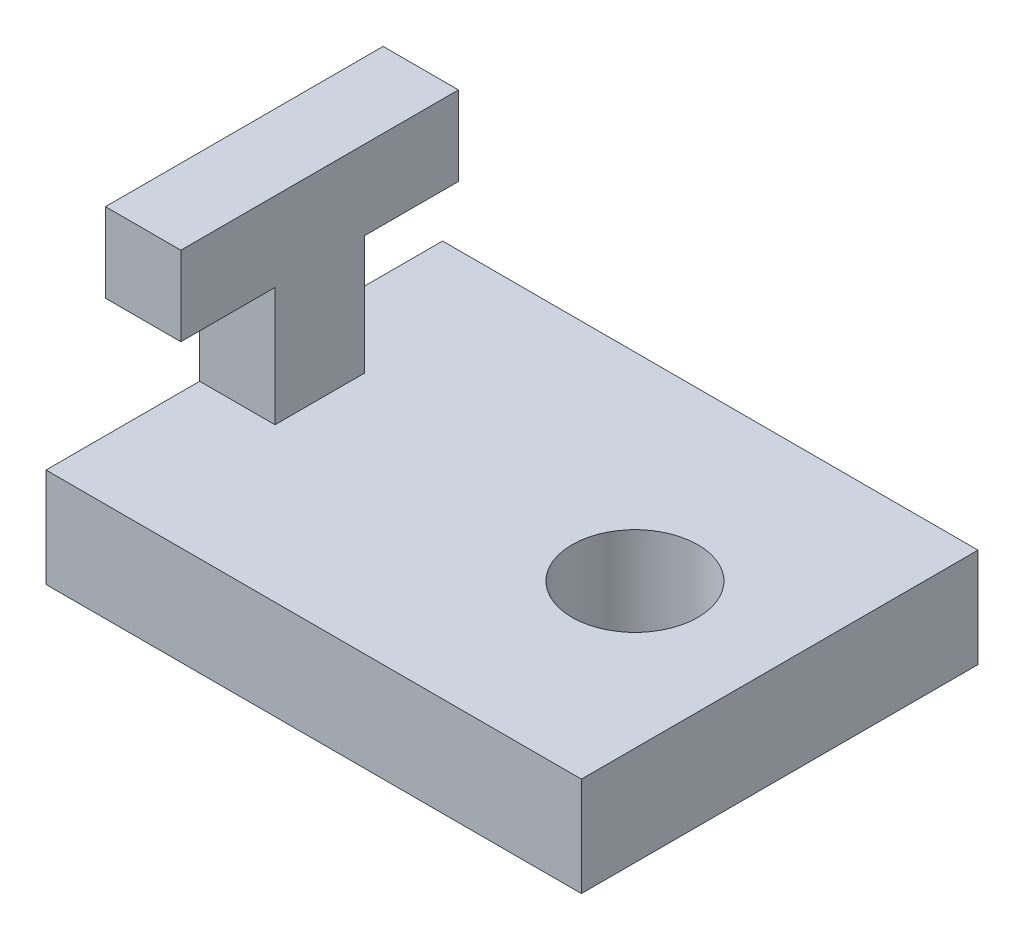
SolidWorks part; units mm, degrees
ref_plane "Front Plane" through (0, 0, 0) normal (0, 0, 1) x (1, 0, 0)
ref_plane "Top Plane" through (0, 0, 0) normal (0, 1, 0) x (1, 0, 0)
ref_plane "Right Plane" through (0, 0, 0) normal (1, 0, 0) x (0, 0, -1)
sketch "Sketch1" plane through (0, 0, 0) normal (0, 1, 0) x (1, 0, 0)
  line L1 (13.5, -10) -> (-13.5, -10)
  line L2 (13.5, -10) -> (13.5, 10)
  line L3 (13.5, 10) -> (-13.5, 10)
  line L4 (-13.5, -10) -> (-13.5, 10)
  line L5 (13.5, -10) -> (-13.5, 10) construction
  line L6 (13.5, 10) -> (-13.5, -10) construction
  point P0 (0, 0)
  dimension "D1" = 20
  dimension "D2" = 27
extrude "Boss-Extrude1" add sketch "Sketch1" along normal blind 5
sketch "Sketch2" plane through (-13.5, 0, 0) normal (-1, 0, 0) x (0, 0, 1)
  line L0 (2.25, 5) -> (-2.25, 5)
  line L1 (-10, 5) -> (10, 5) construction
  line L2 (-2.25, 5) -> (-2.25, 11)
  line L3 (-2.25, 11) -> (-7, 11)
  line L4 (-7, 11) -> (-7, 15)
  line L5 (-7, 15) -> (7, 15)
  line L6 (7, 15) -> (7, 11)
  line L7 (7, 11) -> (2.25, 11)
  line L8 (2.25, 11) -> (2.25, 5)
  point P5 (0, 5)
  point P11 (0, 0)
  point P12 (0, 0)
  point P13 (0, 5)
  dimension "D1" = 6
  dimension "D2" = 4
  dimension "D3" = 14
  dimension "D4" = 4.5
extrude "Boss-Extrude2" add sketch "Sketch2" against normal blind 3.8 separate body
sketch "Sketch3" plane through (0, 0, 0) normal (0, -1, 0) x (1, 0, 0)
  line L0 (13.5, 0) -> (0, 0) construction
  line L1 (13.5, 10) -> (13.5, -10) construction
  line L3 (-6.5, -2.54) -> (-6.5, -15.96) construction
  circle A0 centre (6.2, 0) radius 3.175
  dimension "D2" = 6.35
  dimension "D1" = 12.7
extrude "Cut-Extrude1" cut sketch "Sketch3" against normal blind 10
